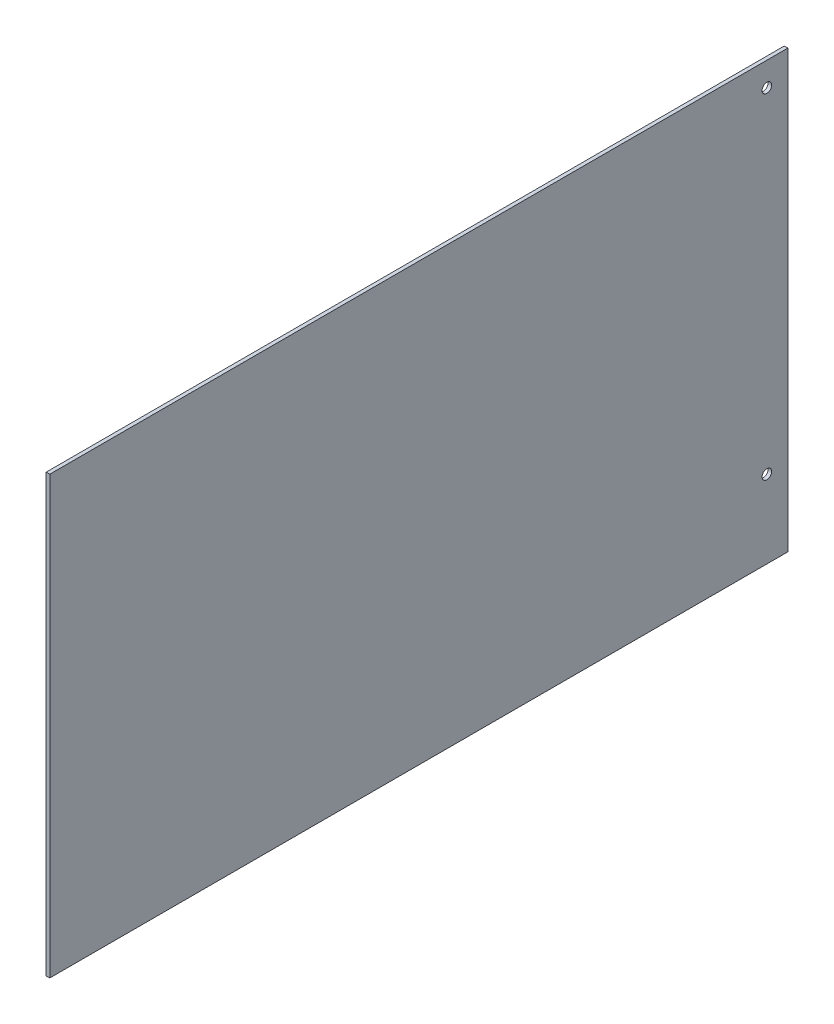
SolidWorks part; units mm, degrees
ref_plane "Front Plane" through (0, 0, 0) normal (0, 0, 1) x (1, 0, 0)
ref_plane "Top Plane" through (0, 0, 0) normal (0, 1, 0) x (1, 0, 0)
ref_plane "Right Plane" through (0, 0, 0) normal (1, 0, 0) x (0, 0, -1)
sketch "Sketch1" plane through (0, 0, 0) normal (1, 0, 0) x (0, 0, -1)
  line L0 (0, 0) -> (0, 261.6027) construction
  line L1 (-392.5938, 156.1869) -> (224.5062, 156.1869)
  line L2 (-392.5938, 156.1869) -> (-392.5938, -208.6131)
  line L3 (-392.5938, -208.6131) -> (224.5062, -208.6131)
  line L4 (224.5062, 156.1869) -> (224.5062, -208.6131)
  line L6 (0, 0) -> (224.5062, 156.1869) construction
  line L7 (0, 0) -> (0, -348.4273) construction
  line L8 (-293.2559, 0) -> (318.1829, 0) construction
  point P0 (0, 0)
  dimension "D1" = 617.1
  dimension "D2" = 364.8
extrude "Boss-Extrude1" add sketch "Sketch1" along normal blind 3
sketch "Sketch2" plane through (0, 0, 0) normal (-1, 0, 0) x (0, 0, 1)
  line L0 (-224.5062, -208.6131) -> (-224.5062, 156.1869) construction
  line L1 (392.5938, -208.6131) -> (-224.5062, -208.6131) construction
  line L2 (-224.5062, 156.1869) -> (392.5938, 156.1869) construction
  circle A0 centre (-207.0062, -143.6131) radius 4
  circle A1 centre (-207.0062, 136.1869) radius 4
  dimension "D2" = 8
  dimension "D4" = 8
  dimension "D5" = 17.5
  dimension "D1" = 17.5
  dimension "D3" = 65
  dimension "D6" = 20
extrude "Cut-Extrude1" cut sketch "Sketch2" against normal through all
